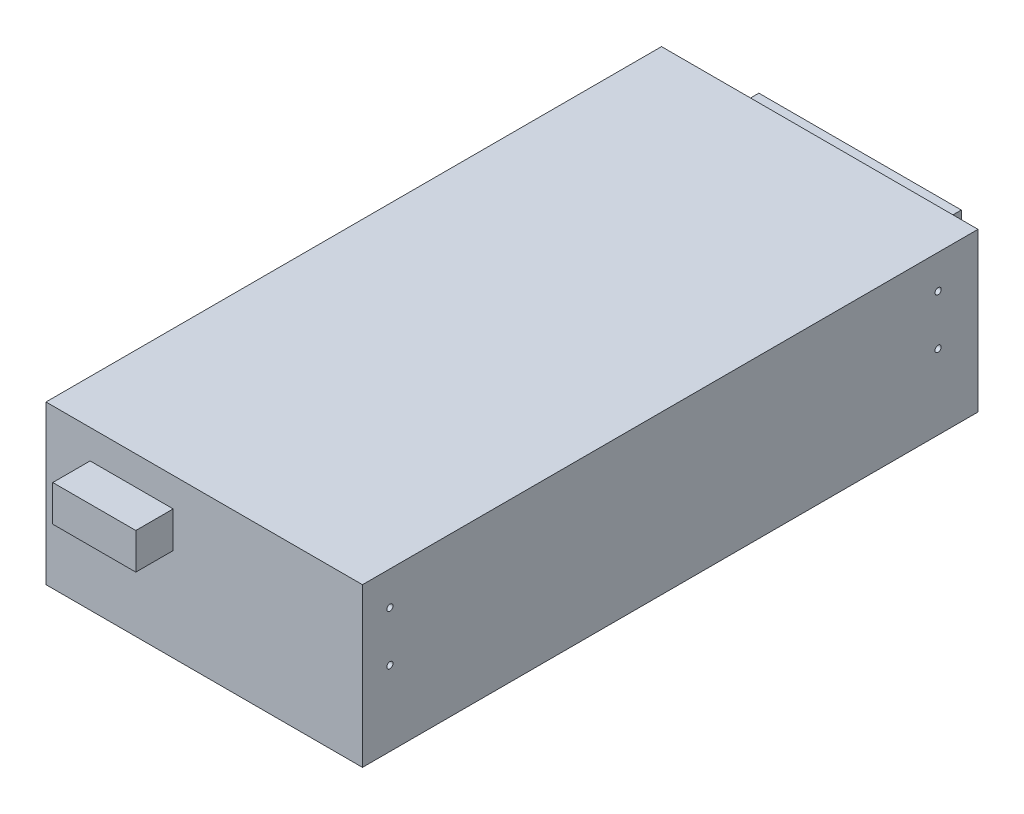
SolidWorks part; units mm, degrees
material "Nylon 6/10"
ref_plane "Front Plane" through (0, 0, 0) normal (0, 0, 1) x (1, 0, 0)
ref_plane "Top Plane" through (0, 0, 0) normal (0, 1, 0) x (1, 0, 0)
ref_plane "Right Plane" through (0, 0, 0) normal (1, 0, 0) x (0, 0, -1)
sketch "Sketch1" plane through (0, 0, 0) normal (0, 1, 0) x (1, 0, 0)
  line L1 (-63.5, 123.5) -> (63.5, 123.5)
  line L2 (-63.5, 123.5) -> (-63.5, -123.5)
  line L3 (-63.5, -123.5) -> (63.5, -123.5)
  line L4 (63.5, 123.5) -> (63.5, -123.5)
  line L5 (-63.5, 123.5) -> (63.5, -123.5) construction
  line L6 (-63.5, -123.5) -> (63.5, 123.5) construction
  point P0 (0, 0)
  dimension "D1" = 127
  dimension "D2" = 247
extrude "Boss-Extrude1" add sketch "Sketch1" along normal blind 63.5
hole_wizard "M3x0.5 Tapped Hole1" positions "Sketch3" profile "Sketch4" tap size "M3x0.5" standard "ANSI Metric"
sketch "Sketch3" plane through (63.5, 0, 0) normal (1, 0, 0) x (0, 0, -1)
  line L1 (-112.5, 50) -> (107.5, 50)
  line L2 (-112.5, 50) -> (-112.5, 30)
  line L3 (-112.5, 30) -> (107.5, 30)
  line L4 (107.5, 50) -> (107.5, 30)
  line L5 (-123.5, 63.5) -> (-123.5, 0) construction
  line L6 (-123.5, 0) -> (123.5, 0) construction
  point P1 (-112.5, 50)
  point P2 (107.5, 30)
  point P85 (-112.5, 30)
  point P86 (107.5, 50)
  dimension "D1" = 11
  dimension "D2" = 220
  dimension "D3" = 20
  dimension "D4" = 30
sketch "Sketch4" plane through (63.5, 50, 112.5) normal (0, 1, 0) x (0, 0, -1)
  line L0 (0, 0) -> (0, 4.7511)
  line L1 (0, 4.7511) -> (1.25, 4)
  line L2 (1.25, 4) -> (1.25, 0)
  line L5 (1.25, 0) -> (0, 0)
  line L10 (0, 4.7511) -> (-1.25, 4) construction
  line L11 (0, -6.35) -> (0, 107.95) construction
  dimension "Tap Drill Dia." = 2.5
  dimension "Tap Drill Depth" = 4
  dimension "Drill Angle" = 118
cosmetic thread "Hole Thread1" parameters "D1"=4.5, "D2"=3
cosmetic thread "Hole Thread2" parameters "D1"=4.5, "D2"=3
cosmetic thread "Hole Thread3" parameters "D1"=4.5, "D2"=3
cosmetic thread "Hole Thread4" parameters "D1"=4.5, "D2"=3
sketch "Sketch5" plane through (0, 0, 123.5) normal (0, 0, 1) x (1, 0, 0)
  line L1 (-45.7921, 51.8621) -> (-12.4593, 51.8621)
  line L2 (-45.7921, 51.8621) -> (-45.7921, 37.3801)
  line L3 (-45.7921, 37.3801) -> (-12.4593, 37.3801)
  line L4 (-12.4593, 51.8621) -> (-12.4593, 37.3801)
extrude "Boss-Extrude2" add sketch "Sketch5" along normal blind 15
sketch "Sketch6" plane through (0, 0, -123.5) normal (0, 0, -1) x (-1, 0, 0)
  line L1 (-39.8052, 49.8627) -> (41.4233, 49.8627)
  line L2 (-39.8052, 49.8627) -> (-39.8052, 39.7496)
  line L3 (-39.8052, 39.7496) -> (41.4233, 39.7496)
  line L4 (41.4233, 49.8627) -> (41.4233, 39.7496)
extrude "Boss-Extrude3" add sketch "Sketch6" along normal blind 17
mirror "Mirror1" about plane through (0, 0, 0) normal (1, 0, 0) of "M3x0.5 Tapped Hole1"
cosmetic thread "Hole Thread5" parameters "D1"=4.5, "D2"=3
cosmetic thread "Hole Thread6" parameters "D1"=4.5, "D2"=3
cosmetic thread "Hole Thread7" parameters "D1"=4.5, "D2"=3
cosmetic thread "Hole Thread8" parameters "D1"=4.5, "D2"=3
